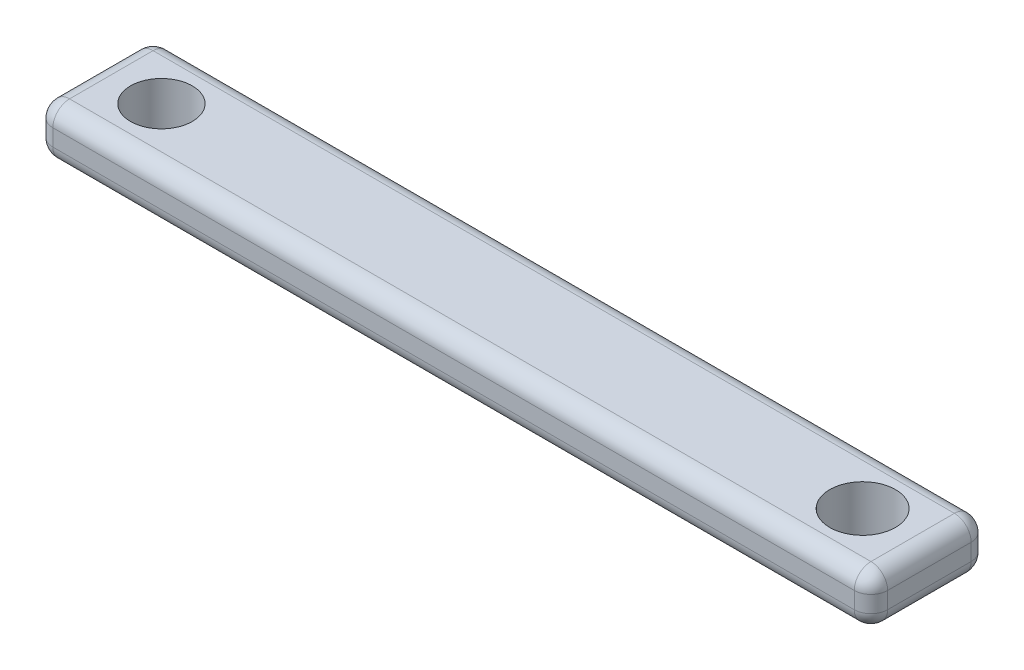
SolidWorks part; units mm, degrees
ref_plane "Front Plane" through (0, 0, 0) normal (0, 0, 1) x (1, 0, 0)
ref_plane "Top Plane" through (0, 0, 0) normal (0, 1, 0) x (1, 0, 0)
ref_plane "Right Plane" through (0, 0, 0) normal (1, 0, 0) x (0, 0, -1)
sketch "Sketch1" plane through (0, 0, 0) normal (0, 1, 0) x (1, 0, 0)
  line L1 (-36.5492, 17.7758) -> (26.9508, 17.7758)
  line L2 (-36.5492, 17.7758) -> (-36.5492, 8.8858)
  line L3 (-36.5492, 8.8858) -> (26.9508, 8.8858)
  line L4 (26.9508, 17.7758) -> (26.9508, 8.8858)
  dimension "D1" = 63.5
  dimension "D2" = 8.89
extrude "Boss-Extrude1" add sketch "Sketch1" along normal blind 3.81
fillet "Fillet1" radius 1.27 12 edges at (-36.5492, 3.81, -13.3308) (-36.5492, 0, -13.3308) (-4.7992, 3.81, -17.7758) (-36.5492, 1.905, -17.7758) (-4.7992, 0, -17.7758) (26.9508, 3.81, -13.3308) (26.9508, 1.905, -17.7758) (26.9508, 0, -13.3308) (-36.5492, 1.905, -8.8858) (-4.7992, 3.81, -8.8858) (26.9508, 1.905, -8.8858) (-4.7992, 0, -8.8858)
sketch "Sketch2" plane through (0, 3.81, 0) normal (0, 1, 0) x (1, 0, 0)
  line L0 (-35.2792, 16.5058) -> (-35.2792, 10.1558) construction
  line L1 (25.6808, 10.1558) -> (25.6808, 16.5058) construction
  circle A0 centre (-31.4692, 13.3308) radius 2.35
  circle A1 centre (21.8708, 13.3308) radius 2.5
  point P6 (-35.2792, 13.3308)
  dimension "D1" = 5
  dimension "D2" = 3.81
  dimension "D3" = 3.81
extrude "Cut-Extrude1" cut sketch "Sketch2" against normal through all
